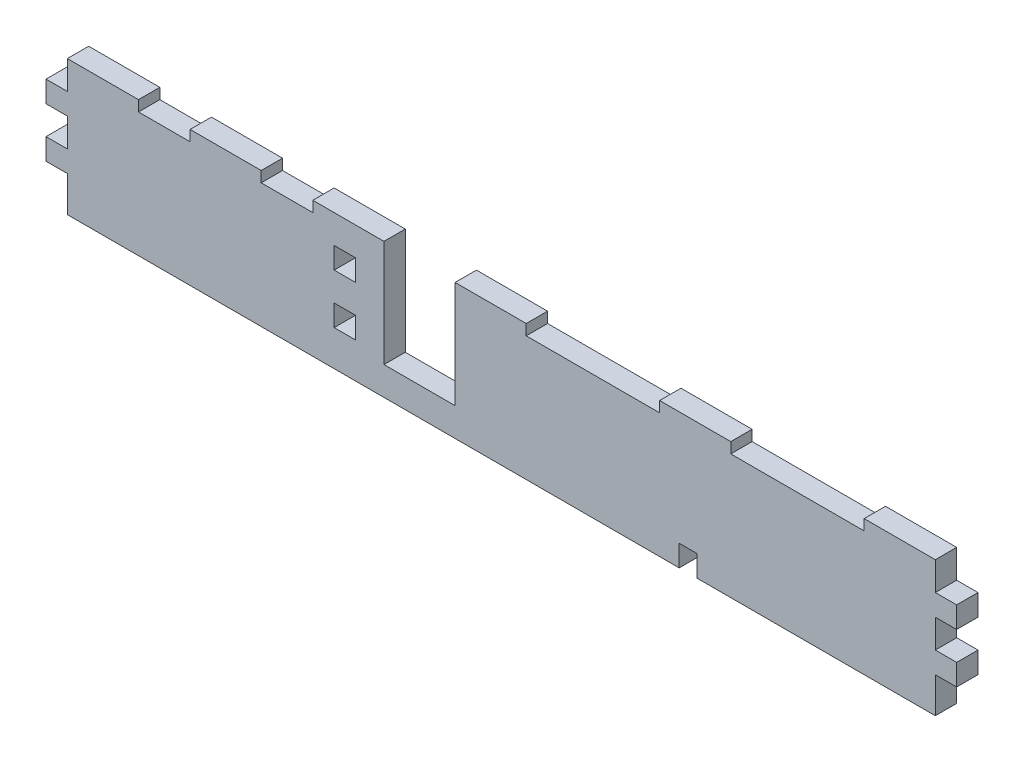
SolidWorks part; units mm, degrees
ref_plane "Спереди" through (0, 0, 0) normal (0, 0, 1) x (1, 0, 0)
ref_plane "Сверху" through (0, 0, 0) normal (0, 1, 0) x (1, 0, 0)
ref_plane "Справа" through (0, 0, 0) normal (1, 0, 0) x (0, 0, -1)
sketch "Эскиз2" plane through (0, 0, 0) normal (0, 0, 1) x (1, 0, 0)
  line L0 (89, 38) -> (89, 8)
  line L1 (0, 0) -> (172, 0)
  line L2 (0, 0) -> (0, 38) construction
  line L3 (0, 38) -> (20, 38)
  line L4 (244, 0) -> (244, 38) construction
  line L5 (89, 8) -> (109, 8)
  line L6 (109, 8) -> (109, 38)
  line L7 (0, 35) -> (244, 35) construction
  line L8 (0, 22) -> (244, 22) construction
  line L10 (244, 30) -> (250, 30)
  line L11 (250, 30) -> (250, 24)
  line L12 (250, 24) -> (244, 24)
  line L13 (244, 24) -> (244, 16)
  line L14 (244, 16) -> (250, 16)
  line L15 (250, 16) -> (250, 10)
  line L16 (250, 10) -> (244, 10)
  line L17 (244, 10) -> (244, 0)
  line L18 (244, 38) -> (244, 30)
  line L19 (0, 0) -> (0, 10)
  line L20 (0, 10) -> (-6, 10)
  line L21 (-6, 10) -> (-6, 16)
  line L22 (-6, 16) -> (0, 16)
  line L23 (0, 16) -> (0, 24)
  line L24 (0, 24) -> (-6, 24)
  line L25 (-6, 24) -> (-6, 30)
  line L26 (-6, 30) -> (0, 30)
  line L27 (0, 30) -> (0, 38)
  line L28 (109, 38) -> (129, 38)
  line L29 (81, 30) -> (75, 30)
  line L30 (81, 30) -> (81, 24)
  line L31 (81, 24) -> (75, 24)
  line L32 (75, 30) -> (75, 24)
  line L33 (81, 16) -> (75, 16)
  line L34 (81, 16) -> (81, 10)
  line L35 (81, 10) -> (75, 10)
  line L36 (75, 16) -> (75, 10)
  line L37 (129, 38) -> (129, 35)
  line L38 (129, 35) -> (166.5, 35)
  line L39 (166.5, 35) -> (166.5, 38)
  line L40 (166.5, 38) -> (186.5, 38)
  line L41 (186.5, 38) -> (186.5, 35)
  line L42 (186.5, 35) -> (224, 35)
  line L43 (224, 35) -> (224, 38)
  line L44 (224, 38) -> (244, 38)
  line L45 (109, 16) -> (244, 16) construction
  line L46 (34.5, 38) -> (54.5, 38)
  line L48 (20, 38) -> (20, 35)
  line L49 (20, 35) -> (34.5, 35)
  line L50 (34.5, 38) -> (34.5, 35)
  line L52 (54.5, 38) -> (54.5, 35)
  line L53 (54.5, 35) -> (69, 35)
  line L54 (69, 38) -> (69, 35)
  line L55 (69, 38) -> (89, 38)
  line L56 (177, 0) -> (244, 0)
  line L57 (0, 16) -> (89, 16) construction
  line L59 (172, 0) -> (172, 6)
  line L60 (172, 6) -> (177, 6)
  line L61 (177, 0) -> (177, 6)
  point P46 (176.5, 16)
  point P47 (176.5, 38)
  point P56 (44.5, 16)
  point P58 (44.5, 38)
  dimension "D1" = 244
  dimension "D2" = 38
  dimension "D3" = 20
  dimension "D4" = 30
  dimension "D5" = 3
  dimension "D6" = 16
  dimension "D7" = 89
  dimension "D8" = 6
  dimension "D9" = 6
  dimension "D10" = 10
  dimension "D11" = 8
  dimension "D12" = 6
  dimension "D13" = 6
  dimension "D14" = 6
  dimension "D15" = 8
  dimension "D16" = 20
  dimension "D17" = 20
  dimension "D18" = 20
  dimension "D19" = 20
  dimension "D20" = 20
  dimension "D21" = 20
  dimension "D22" = 67
  dimension "D23" = 5
  dimension "D24" = 6
extrude "Бобышка-Вытянуть1" add sketch "Эскиз2" along normal blind 6
